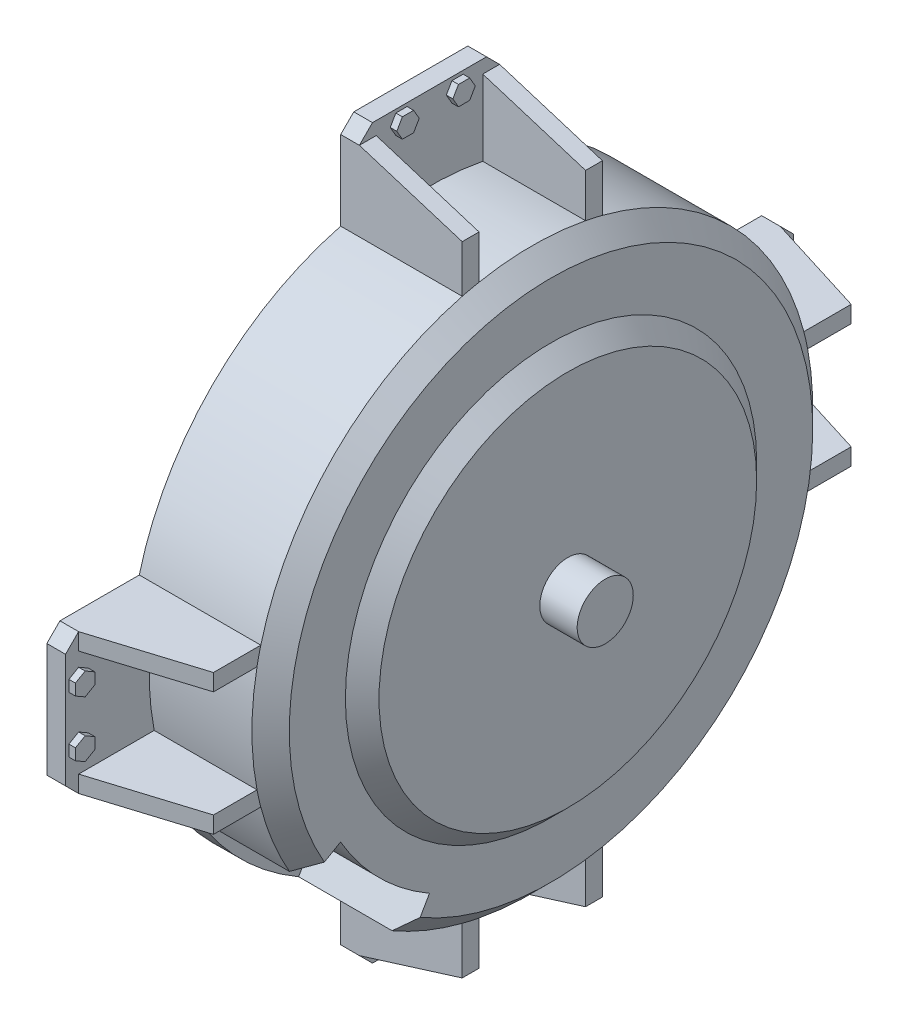
SolidWorks part; units mm, degrees
ref_plane "Front Plane" through (0, 0, 0) normal (0, 0, 1) x (1, 0, 0)
ref_plane "Top Plane" through (0, 0, 0) normal (0, 1, 0) x (1, 0, 0)
ref_plane "Right Plane" through (0, 0, 0) normal (1, 0, 0) x (0, 0, -1)
sketch "Sketch2" plane through (0, 0, 0) normal (1, 0, 0) x (0, 0, -1)
  circle A0 centre (0, 0) radius 150
  dimension "D1" = 300
extrude "Boss-Extrude1" add sketch "Sketch2" along normal blind 75
chamfer "Chamfer1" distance 10 angle 45 1 edges at (75, 0, -150)
sketch "Sketch3" plane through (0, 0, 0) normal (-1, 0, 0) x (0, 0, 1)
  line L1 (-37.5, 144.6895) -> (-37.5, 194.6895)
  line L2 (37.5, 144.6895) -> (37.5, 194.6895)
  line L3 (-37.5, 194.6895) -> (37.5, 194.6895)
  arc A0 (37.5, 144.6895) -> (-37.5, 144.6895) centre (0, 0) ccw
  dimension "D3" = 50
extrude "Boss-Extrude2" add sketch "Sketch3" against normal blind 10
chamfer "Chamfer2" distance 7 angle 45 2 edges at (5, 194.6895, -37.5) (5, 194.6895, 37.5)
sketch "Sketch4" plane through (0, 0, -37.5) normal (0, 0, -1) x (-1, 0, 0)
  line L0 (-10, 145.2369) -> (-10, 187.6895)
  line L1 (-10, 145.2369) -> (-65, 145.2369)
  line L2 (-65, -150) -> (-65, 150) construction
  line L3 (-65, 145.2369) -> (-65, 170.5569)
  line L4 (-65, 170.5569) -> (-10, 187.6895)
  dimension "D1" = 25.32
extrude "Boss-Extrude3" add sketch "Sketch4" against normal blind 9
sketch "Sketch5" plane through (10, 0, 0) normal (1, 0, 0) x (0, 0, -1)
  line L0 (0, 150) -> (0, 228.237) construction
  line L1 (37.5, 187.6895) -> (-37.5, 187.6895) construction
  line L9 (21, 187.6895) -> (18, 192.8856)
  line L10 (18, 192.8856) -> (12, 192.8856)
  line L11 (12, 192.8856) -> (9, 187.6895)
  line L12 (9, 187.6895) -> (12, 182.4933)
  line L13 (12, 182.4933) -> (18, 182.4933)
  line L14 (18, 182.4933) -> (21, 187.6895)
  arc A0 (28.5, 147.2676) -> (37.5, 145.2369) centre (0, 0) ccw construction
  arc A1 (28.5, 147.2676) -> (-37.5, 145.2369) centre (0, 0) ccw construction
  circle A2 centre (15, 187.6895) radius 5.1962 construction
  dimension "D1" = 6
  dimension "D2" = 13.5
extrude "Boss-Extrude4" add sketch "Sketch5" along normal blind 3.5
mirror "Mirror1" about plane through (0, 0, 0) normal (0, 0, 1) of "Boss-Extrude4"
mirror "Mirror2" about plane through (0, 0, 0) normal (0, 0, 1) of "Boss-Extrude3"
pattern_circular "CirPattern1" count 4 over 360 about axis through (0, 0, 0) along (1, 0, 0) of "Boss-Extrude2", "Boss-Extrude3", "Boss-Extrude4", "Mirror1", "Mirror2", "Chamfer2"
sketch "Sketch7" plane through (75, 0, 0) normal (1, 0, 0) x (0, 0, -1)
  line L0 (0, 0) -> (247.9041, 0) construction
  line L1 (0, 0) -> (-305.6842, 0) construction
  line L2 (0, 0) -> (0, -220.9081) construction
  line L3 (0, 0) -> (0, 261.788) construction
  line L4 (-112.5833, -65) -> (-121.2436, -70)
  line L5 (-65, -112.5833) -> (-70, -121.2436)
  line L6 (-70, -121.2436) -> (-75, -129.9038)
  line L7 (-121.2436, -70) -> (-129.9038, -75)
  arc A0 (-112.5833, -65) -> (-65, -112.5833) centre (0, 0) ccw
  arc A3 (0, -130) -> (-130, 0) centre (0, 0) ccw
  arc A4 (0, -140) -> (-140, 0) centre (0, 0) ccw
  arc A5 (-145.2369, -37.5) -> (-37.5, -145.2369) centre (0, 0) ccw construction
  arc A6 (-129.9038, -75) -> (-75, -129.9038) centre (0, 0) ccw
  circle M10 centre (0, 0) radius 140
  dimension "D1" = 260
  dimension "D2" = 30
  dimension "D3" = 30
extrude "Cut-Extrude1" cut sketch "Sketch7" against normal blind 60 contours L7 A6 L6 M10 | A0 L4 L5 M10
sketch "Sketch8" plane through (75, 0, 0) normal (1, 0, 0) x (0, 0, -1)
  circle A0 centre (0, 0) radius 110
  dimension "D1" = 220
extrude "Boss-Extrude5" add sketch "Sketch8" along normal blind 9 draft 45
sketch "Sketch9" plane through (84, 0, 0) normal (1, 0, 0) x (0, 0, -1)
  circle A1 centre (0, 0) radius 15
  dimension "D1" = 30
extrude "Boss-Extrude6" add sketch "Sketch9" along normal blind 20
